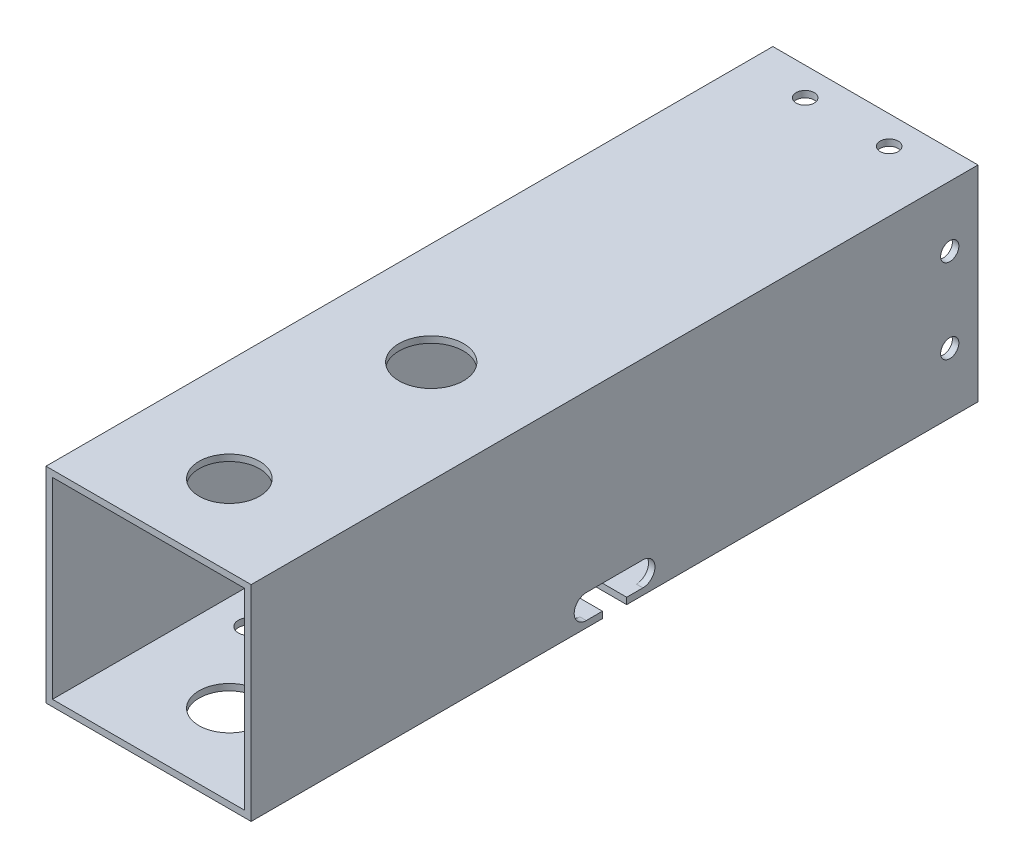
SolidWorks part; units mm, degrees
ref_plane "Front Plane" through (0, 0, 0) normal (0, 0, 1) x (1, 0, 0)
ref_plane "Top Plane" through (0, 0, 0) normal (0, 1, 0) x (1, 0, 0)
ref_plane "Right Plane" through (0, 0, 0) normal (1, 0, 0) x (0, 0, -1)
sketch "Sketch1" plane through (0, 0, 0) normal (0, 0, 1) x (1, 0, 0)
  line L0 (-23.8, 23.8) -> (23.8, 23.8)
  line L1 (-25.4, -25.4) -> (25.4, -25.4)
  line L2 (-25.4, -25.4) -> (-25.4, 25.4)
  line L3 (-25.4, 25.4) -> (25.4, 25.4)
  line L4 (25.4, -25.4) -> (25.4, 25.4)
  line L5 (-25.4, -25.4) -> (25.4, 25.4) construction
  line L6 (-25.4, 25.4) -> (25.4, -25.4) construction
  line L7 (23.8, -23.8) -> (23.8, 23.8)
  line L8 (-23.8, -23.8) -> (23.8, -23.8)
  line L9 (-23.8, -23.8) -> (-23.8, 23.8)
  point P0 (0, 0)
  dimension "D1" = 50.8
  dimension "D2" = 50.8
  dimension "D3" = 1.6
extrude "Boss-Extrude1" add sketch "Sketch1" along normal blind 180
sketch "Sketch2" plane through (0, 0, 0) normal (0, 0, 1) x (1, 0, 0)
  point P0 (0, 0)
sketch "Sketch3" plane through (0, 0, 0) normal (1, 0, 0) x (0, 0, -1)
  line L0 (0, 0) -> (-143.944, 0) construction
ref_plane "Plane1" through (0, 0, 66) normal (0, 0, 1) x (1, 0, 0)
sketch "Sketch6" plane through (0, 25.4, 0) normal (0, 1, 0) x (1, 0, 0)
  line L0 (0, -110) -> (0, -160) construction
  line L1 (25.4, -143.1653) -> (-25.4, -143.1653) construction
  line L2 (25.4, -180) -> (25.4, 0) construction
  line L3 (-25.4, -180) -> (-25.4, 0) construction
  line L4 (25.4, -180) -> (-25.4, -180) construction
  circle A0 centre (0, -160) radius 7.5
  circle A1 centre (0, -110) radius 8
  point P11 (0, -143.1653)
  dimension "D1" = 15
  dimension "D2" = 16
  dimension "D3" = 20
  dimension "D4" = 70
extrude "Cut-Extrude1" cut sketch "Sketch6" against normal through all
hole_wizard "M4 Clearance Hole1" positions "Sketch7" profile "Sketch8" hole size "M4" standard "ISO"
sketch "Sketch7" plane through (-25.4, 0, 0) normal (-1, 0, 0) x (0, 0, 1)
  point P0 (7, -10.4)
  point P2 (7, 10.4)
  dimension "D1" = 7
  dimension "D2" = 15
  dimension "D3" = 15
  dimension "D4" = 7
sketch "Sketch8" plane through (-25.4, -10.4, 7) normal (0, 1, 0) x (0, 0, 1)
  line L0 (0, 0) -> (0, 12.8519)
  line L1 (0, 12.8519) -> (2.25, 11.5)
  line L2 (2.25, 11.5) -> (2.25, 0)
  line L5 (2.25, 0) -> (0, 0)
  line L10 (0, 12.8519) -> (-2.25, 11.5) construction
  line L11 (0, -6.35) -> (0, 107.95) construction
  dimension "Hole Dia." = 4.5
  dimension "Hole Depth" = 11.5
  dimension "Drill Angle" = 118
sketch "Sketch10" plane through (0, 0, 0) normal (1, 0, 0) x (0, 0, -1)
  line L0 (0, 0) -> (-184.0234, 0) construction
pattern_circular "CirPattern1" count 4 every 90 about axis through (0, 0, 0) along (0, 0, 1) of "M4 Clearance Hole1"
hole_wizard "M5 Clearance Hole1" positions "Sketch11" profile "Sketch12" hole size "M5" standard "ISO"
sketch "Sketch11" plane through (0, -25.4, 0) normal (0, 1, 0) x (1, 0, 0)
  line L0 (0, -110) -> (0, -160) construction
  line L9 (0, -160) -> (17.4515, -160) construction
  circle A0 centre (0, -110) radius 8 construction
  point P0 (15, -140)
  point P19 (-15, -140)
  point P23 (-15, -45.7)
  point P41 (15, -45.7)
  dimension "D1" = 64.3
  dimension "D2" = 20
sketch "Sketch12" plane through (15, -25.4, 140) normal (1, 0, 0) x (0, 0, -1)
  line L0 (0, 0) -> (0, 21.4024)
  line L1 (0, 21.4024) -> (2.75, 19.75)
  line L2 (2.75, 19.75) -> (2.75, 0)
  line L5 (2.75, 0) -> (0, 0)
  line L10 (0, 21.4024) -> (-2.75, 19.75) construction
  line L11 (0, -6.35) -> (0, 107.95) construction
  dimension "Hole Dia." = 5.5
  dimension "Hole Depth" = 19.75
  dimension "Drill Angle" = 118
sketch "Sketch13" plane through (0, -25.4, 0) normal (0, -1, 0) x (-1, 0, 0)
  line L0 (-13, -90) -> (-25.4, -90) construction
  line L1 (-25.4, -180) -> (-25.4, 0) construction
  line L2 (-13, -93) -> (-25.4, -93)
  line L3 (-13, -87) -> (-25.4, -87)
  line L4 (0, -160) -> (-13.616, -160) construction
  line L5 (0, -160) -> (0, -145.918) construction
  arc A0 (-13, -93) -> (-13, -87) centre (-13, -90) ccw
  arc A1 (-25.4, -87) -> (-25.4, -93) centre (-25.4, -90) ccw
  point P4 (-19.2, -90)
  dimension "D1" = 70
  dimension "D3" = 3
  dimension "D2" = 13
extrude "Cut-Extrude2" cut sketch "Sketch13" against normal up to surface (1.6 mm away) up to face at (15, -23.8, 142.75)
sketch "Sketch14" plane through (25.4, 0, 0) normal (1, 0, 0) x (0, 0, -1)
  line L0 (-90, -23.8) -> (-90, -18.3046) construction
  line L1 (-93, -23.8) -> (-87, -23.8) construction
  line L3 (-97, -20.8) -> (-83, -20.8) construction
  line L4 (-97, -17.8) -> (-83, -17.8)
  line L5 (-97, -23.8) -> (-83, -23.8)
  arc A0 (-97, -17.8) -> (-97, -23.8) centre (-97, -20.8) ccw
  arc A1 (-83, -23.8) -> (-83, -17.8) centre (-83, -20.8) ccw
  point P6 (-90, -20.8)
  dimension "D1" = 14
  dimension "D2" = 3
extrude "Cut-Extrude3" cut sketch "Sketch14" against normal up to surface (1.6 mm away) up to face at (23.8, 8.15, 7)
